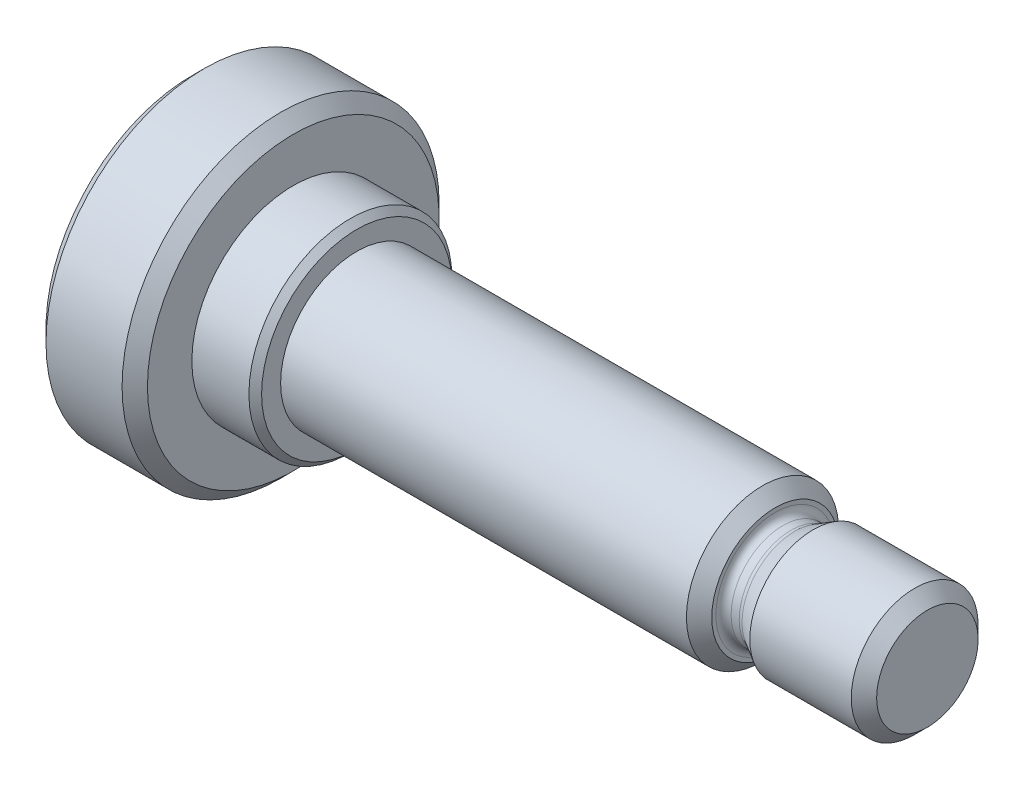
SolidWorks part; units mm, degrees
ref_plane "Piano frontale" through (0, 0, 0) normal (0, 0, 1) x (1, 0, 0)
ref_plane "Piano superiore" through (0, 0, 0) normal (0, 1, 0) x (1, 0, 0)
ref_plane "Piano destro" through (0, 0, 0) normal (1, 0, 0) x (0, 0, -1)
sketch "Sketch1" plane through (0, 0, 0) normal (0, 0, 1) x (1, 0, 0)
  line L0 (0, 0) -> (0, 12.5)
  line L1 (0, 12.5) -> (8, 12.5)
  line L2 (8, 12.5) -> (8, 8)
  line L3 (8, 8) -> (13, 8)
  line L4 (13, 8) -> (13, 6)
  line L5 (13, 6) -> (46, 6)
  line L6 (46, 6) -> (46, 4.0762)
  line L9 (49, 5) -> (58, 5)
  line L10 (58, 5) -> (58, 0)
  line L11 (-9.6761, 0) -> (67.9998, 0) construction
  line L12 (0, 0) -> (58, 0)
  line L13 (49, 5) -> (47.4, 4.0762)
  line L15 (46, 4.0762) -> (47.4, 4.0762)
  point P22 (46, 4.0762)
  dimension "D1" = 12.5
  dimension "D2" = 8
  dimension "D3" = 6
  dimension "D4" = 5
  dimension "D5" = 8
  dimension "D6" = 5
  dimension "D7" = 58
  dimension "D8" = 12
  dimension "D9" = 1.6
  dimension "D10" = 30
  dimension "D11" = 3
revolve "Revolve1" add sketch "Sketch1" angle 360 about L11
cosmetic thread "Cosmetic Thread4" parameters "D2"=8.344
chamfer "Chamfer1" distance 1 angle 45 3 edges at (46, 0, 6) (8, 0, 12.5) (0, 0, 12.5)
fillet "Fillet1" radius 0.6 2 edges at (47.4, 0, 4.0762) (46, 0, 4.0762)
chamfer "Chamfer3" distance 1 angle 45 1 edges at (58, 0, 5)
chamfer "Chamfer4" distance 0.5 angle 45 1 edges at (13, 0, 8)
